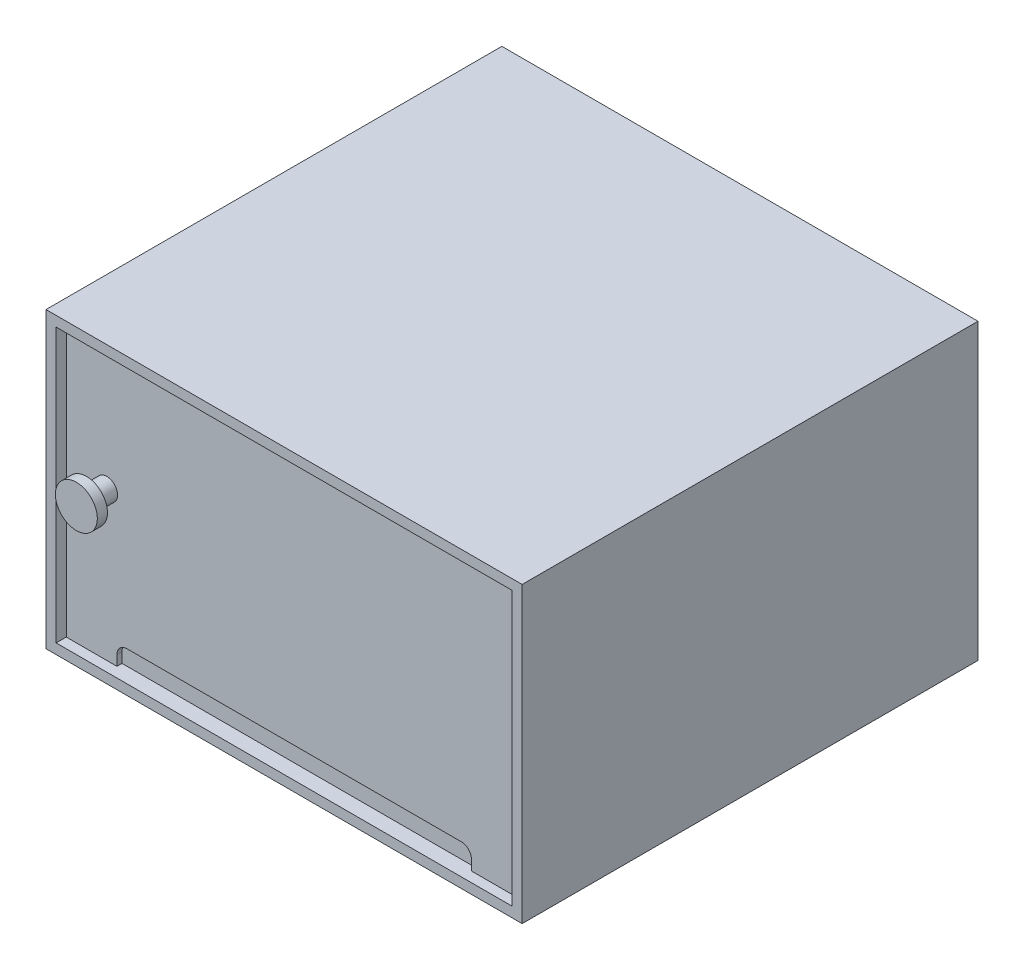
SolidWorks part; units mm, degrees
ref_plane "Front Plane" through (0, 0, 0) normal (0, 0, 1) x (1, 0, 0)
ref_plane "Top Plane" through (0, 0, 0) normal (0, 1, 0) x (1, 0, 0)
ref_plane "Right Plane" through (0, 0, 0) normal (1, 0, 0) x (0, 0, -1)
sketch "Sketch1" plane through (0, 0, 0) normal (0, 1, 0) x (1, 0, 0)
  line L1 (235, -225) -> (-235, -225)
  line L2 (235, -225) -> (235, 225)
  line L3 (235, 225) -> (-235, 225)
  line L4 (-235, -225) -> (-235, 225)
  line L5 (235, -225) -> (-235, 225) construction
  line L6 (235, 225) -> (-235, -225) construction
  point P0 (0, 0)
  dimension "D1" = 470
  dimension "D2" = 450
extrude "Boss-Extrude1" add sketch "Sketch1" along normal blind 290
shell "Shell1" thickness 10
sketch "Sketch2" plane through (0, 0, 225) normal (0, 0, 1) x (1, 0, 0)
  line L0 (-225, 280) -> (225, 280) construction
  line L1 (-225, 280) -> (-225, 10) construction
  line L2 (-225, 10) -> (225, 10) construction
  line L3 (225, 280) -> (225, 10) construction
  line L4 (-225, 280) -> (225, 280)
  line L5 (-225, 280) -> (-225, 10)
  line L6 (-225, 10) -> (225, 10)
  line L7 (225, 280) -> (225, 10)
extrude "Boss-Extrude2" add sketch "Sketch2" along normal blind 10 from offset 20 offset against normal yes
sketch "Sketch3" plane through (0, 0, 215) normal (0, 0, 1) x (1, 0, 0)
  line L0 (-225, 10) -> (225, 10) construction
  line L1 (175, 10) -> (-175, 10)
  line L2 (175, 10) -> (175, 30)
  line L3 (175, 30) -> (-175, 30)
  line L4 (-175, 10) -> (-175, 30)
  line L5 (175, 10) -> (-175, 30) construction
  line L6 (175, 30) -> (-175, 10) construction
  line L7 (0, 0) -> (0, 20) construction
  line L8 (-235, 0) -> (235, 0) construction
  point P0 (0, 20)
  dimension "D1" = 20
  dimension "D2" = 350
extrude "Cut-Extrude1" cut sketch "Sketch3" against normal blind 5
fillet "Fillet1" radius 10 2 edges at (175, 30, 212.5) (-175, 30, 212.5)
sketch "Sketch4" plane through (0, 0, 215) normal (0, 0, 1) x (1, 0, 0)
  circle A0 centre (-185.0278, 156.6737) radius 10.6872
extrude "Boss-Extrude3" add sketch "Sketch4" along normal blind 20
sketch "Sketch5" plane through (0, 0, 235) normal (0, 0, 1) x (1, 0, 0)
  circle A2 centre (-185.0278, 156.6737) radius 20.6872
  circle A3 centre (-185.0278, 156.6737) radius 20.6872
  dimension "D1" = 10
extrude "Boss-Extrude4" add sketch "Sketch5" along normal blind 10 separate body
